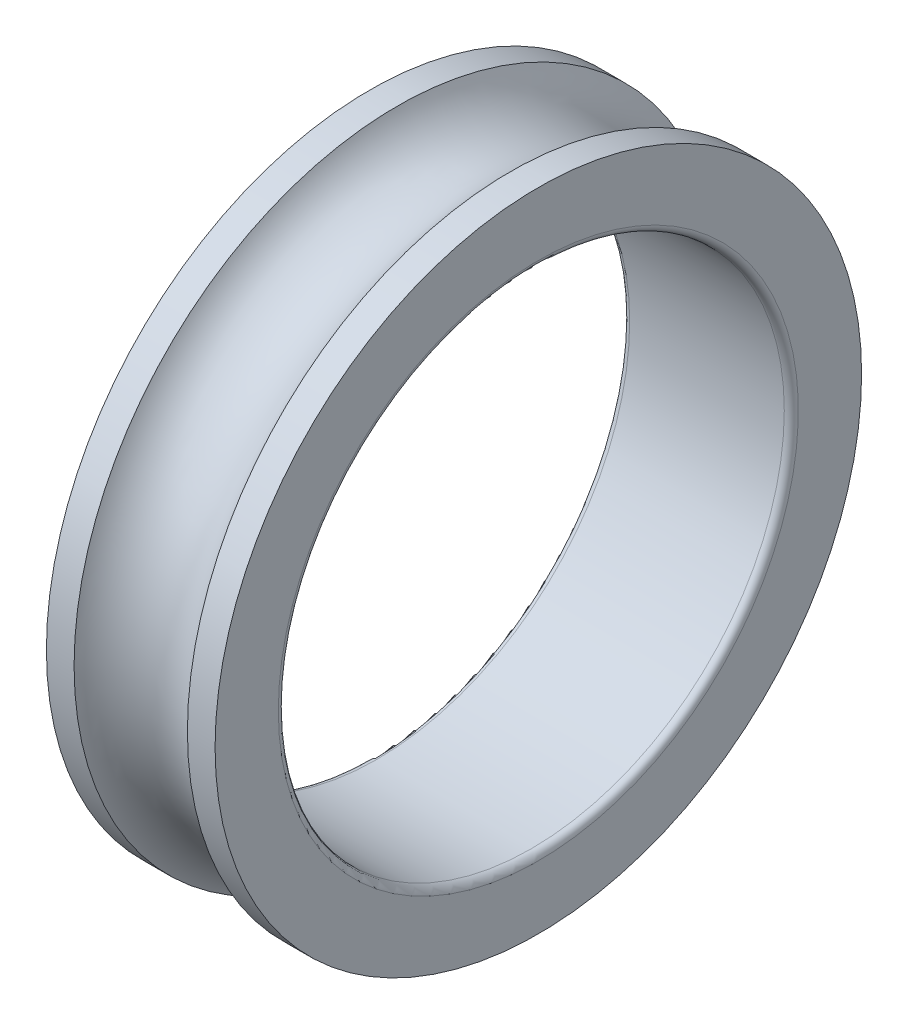
SolidWorks part; units mm, degrees
ref_plane "Front Plane" through (0, 0, 0) normal (0, 0, 1) x (1, 0, 0)
ref_plane "Top Plane" through (0, 0, 0) normal (0, 1, 0) x (1, 0, 0)
ref_plane "Right Plane" through (0, 0, 0) normal (1, 0, 0) x (0, 0, -1)
sketch "Sketch1" plane through (0, 0, 0) normal (0, 0, 1) x (1, 0, 0)
  line L0 (-65.9033, 0) -> (120.5633, 0) construction
  line L1 (0, 0) -> (0, 145.9629) construction
  line L2 (-40.3113, 230) -> (-60, 230)
  line L3 (60, 230) -> (40.3113, 230)
  line L4 (60, 230) -> (60, 180)
  line L5 (60, 180) -> (-60, 180)
  line L6 (-60, 230) -> (-60, 180)
  line L7 (60, 230) -> (-60, 180) construction
  line L8 (60, 180) -> (-60, 230) construction
  arc A0 (-40.3113, 230) -> (40.3113, 230) centre (0, 250) ccw
  point P7 (0, 205)
  dimension "D1" = 90
  dimension "D2" = 250
  dimension "D3" = 50
  dimension "D4" = 120
revolve "Revolve1" add sketch "Sketch1" angle 360 about L0
fillet "Fillet1" radius 5 2 edges at (-60, 0, 180) (60, 0, 180)
scale "Scale1" scale about centroid uniform scaling yes scale factor 0.277778
